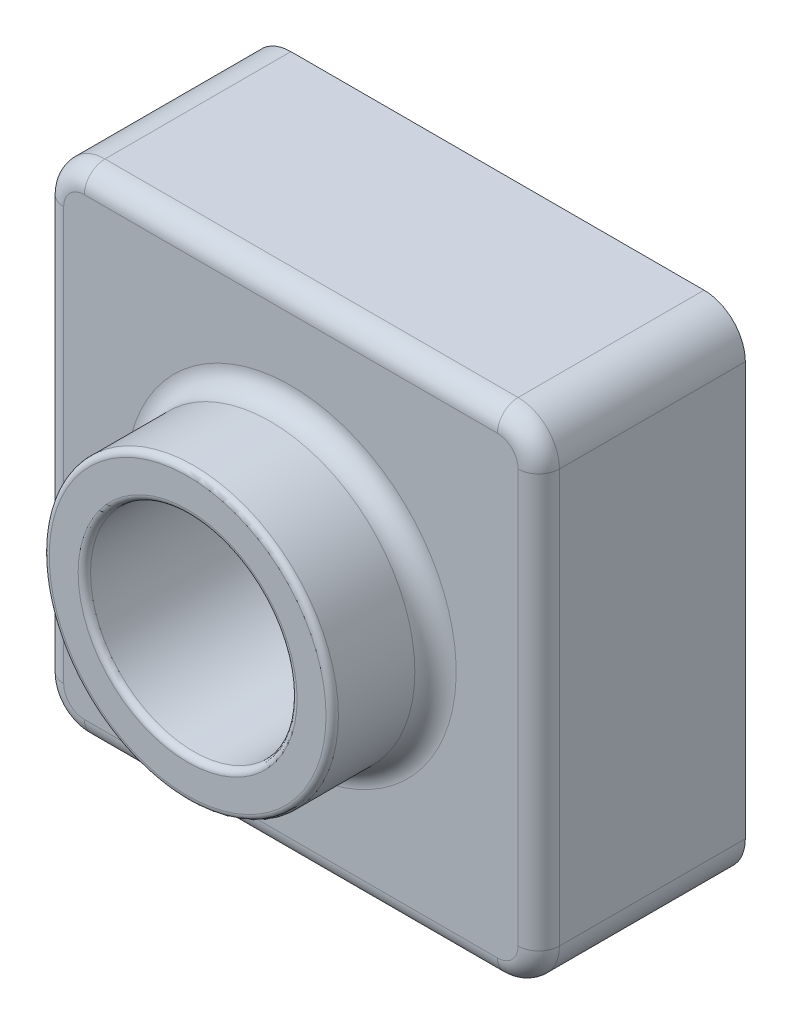
SolidWorks part; units mm, degrees
material "Chrome Stainless Steel"
ref_plane "Front Plane" through (0, 0, 0) normal (0, 0, 1) x (1, 0, 0)
ref_plane "Top Plane" through (0, 0, 0) normal (0, 1, 0) x (1, 0, 0)
ref_plane "Right Plane" through (0, 0, 0) normal (1, 0, 0) x (0, 0, -1)
sketch "Sketch1" plane through (0, 0, 0) normal (0, 0, 1) x (1, 0, 0)
  line L1 (0, 0) -> (120, 0)
  line L2 (0, 0) -> (0, 120)
  line L3 (0, 120) -> (120, 120)
  line L4 (120, 0) -> (120, 120)
  dimension "D1" = 120
  dimension "D2" = 120
extrude "Boss-Extrude1" add sketch "Sketch1" along normal blind 50
sketch "Sketch3" plane through (0, 0, 50) normal (0, 0, 1) x (1, 0, 0)
  line L0 (120, 120) -> (0, 120) construction
  line L1 (0, 120) -> (0, 0) construction
  circle A0 centre (60, 60) radius 35
  dimension "D1" = 70
  dimension "D2" = 60
  dimension "D3" = 60
extrude "Boss-Extrude3" add sketch "Sketch3" along normal blind 25
sketch "Sketch4" plane through (0, 0, 75) normal (0, 0, 1) x (1, 0, 0)
  circle A0 centre (60, 60) radius 25
  dimension "D1" = 50
extrude "Cut-Extrude1" cut sketch "Sketch4" against normal through all
fillet "Fillet1" radius 10 4 edges at (0, 0, 25) (120, 0, 25) (0, 120, 25) (120, 120, 25)
fillet "Fillet2" radius 1.5 2 edges at (95, 60, 75) (85, 60, 75)
fillet "Fillet3" radius 5 9 edges at (2.9289, 117.0711, 50) (60, 120, 50) (117.0711, 117.0711, 50) (120, 60, 50) (117.0711, 2.9289, 50) (60, 0, 50) (2.9289, 2.9289, 50) (0, 60, 50) (95, 60, 50)
shell "Shell1" thickness 2
